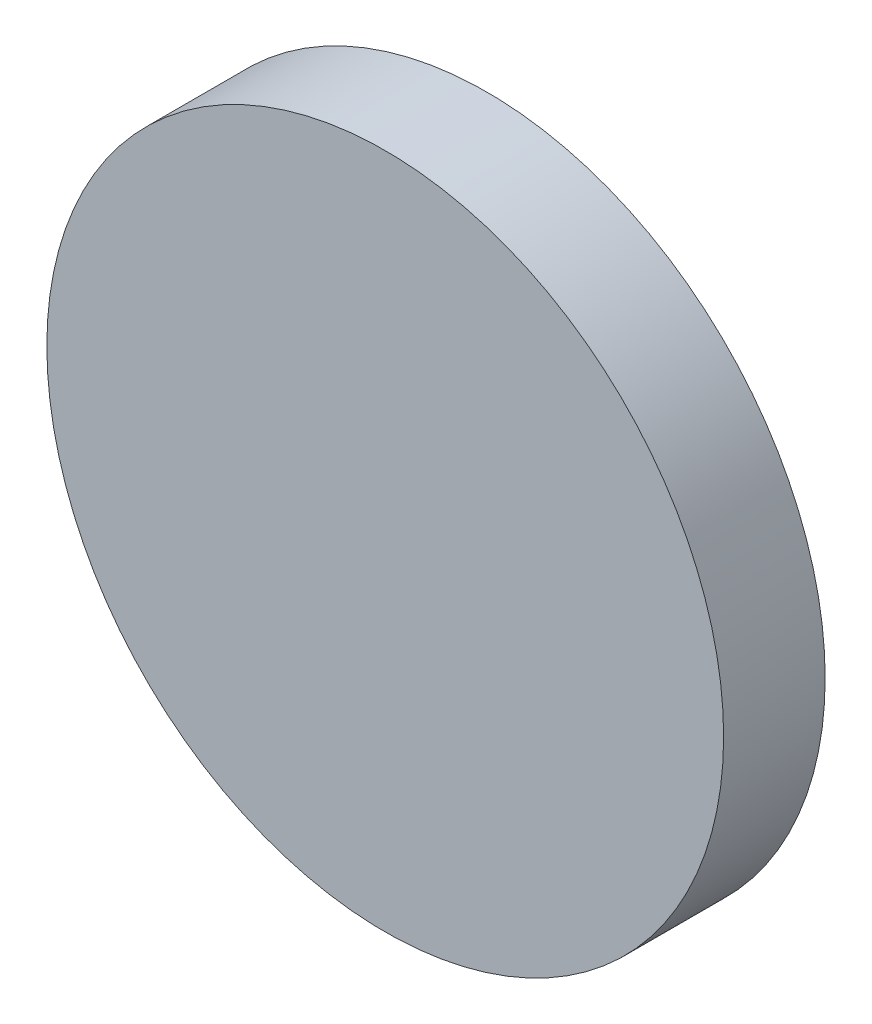
SolidWorks part; units mm, degrees
ref_plane "Plan de face" through (0, 0, 0) normal (0, 0, 1) x (1, 0, 0)
ref_plane "Plan de dessus" through (0, 0, 0) normal (0, 1, 0) x (1, 0, 0)
ref_plane "Plan de droite" through (0, 0, 0) normal (1, 0, 0) x (0, 0, -1)
sketch "Esquisse1" plane through (0, 0, 0) normal (0, 0, 1) x (1, 0, 0)
  circle A0 centre (0, 0) radius 10
  dimension "D1" = 20
extrude "Boss.-Extru.1" add sketch "Esquisse1" along normal blind 3
